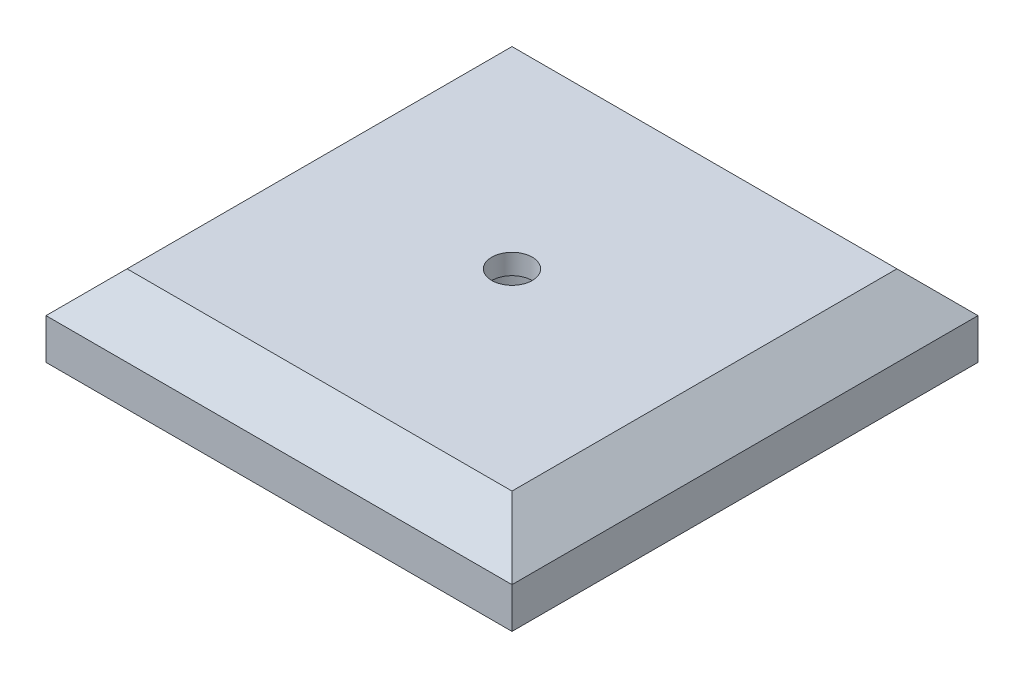
SolidWorks part; units mm, degrees
ref_plane "Front Plane" through (0, 0, 0) normal (0, 0, 1) x (1, 0, 0)
ref_plane "Top Plane" through (0, 0, 0) normal (0, 1, 0) x (1, 0, 0)
ref_plane "Right Plane" through (0, 0, 0) normal (1, 0, 0) x (0, 0, -1)
sketch "Sketch1" plane through (0, 0, 0) normal (0, 1, 0) x (1, 0, 0)
  line L0 (1.4375, 0) -> (1.438, 0) construction
  line L1 (-1.4375, 1.4375) -> (1.4375, 1.4375)
  line L2 (-1.4375, 1.4375) -> (-1.4375, -1.4375)
  line L3 (-1.4375, -1.4375) -> (1.4375, -1.4375)
  line L4 (1.4375, 1.4375) -> (1.4375, -1.4375)
  point P0 (0, 0)
  dimension "D1" = 2.875
  dimension "D2" = 2.875
extrude "Boss-Extrude1" add sketch "Sketch1" along normal blind 0.5
sketch "Sketch4" plane through (0, 0, 0) normal (0, 1, 0) x (1, 0, 0)
  circle A0 centre (0, 0) radius 0.2527
extrude "Cut-Extrude2" cut sketch "Sketch4" along normal blind 0.375
ref_plane "Plane2" through (0, 0.375, 0) normal (0, 1, 0) x (1, 0, 0)
sketch "Sketch6" plane through (0, 0.375, 0) normal (0, 1, 0) x (1, 0, 0)
  circle A0 centre (0, 0) radius 0.125
  dimension "D1" = 0.25
extrude "Cut-Extrude3" cut sketch "Sketch6" along normal blind 0.125 contours A0
ref_plane "Plane3" through (0, 0, 1.438) normal (0, 0, 1) x (1, 0, 0)
chamfer "Chamfer1" distance 0.25 angle 45 1 edges at (0, 0.5, 1.4375)
chamfer "Chamfer2" distance 0.25 angle 45 1 edges at (1.4375, 0.5, -0.125)
chamfer "Chamfer3" distance 0.25 angle 45 1 edges at (-0.125, 0.5, -1.4375)
chamfer "Chamfer4" distance 0.25 angle 45 1 edges at (-1.4375, 0.5, 0)
